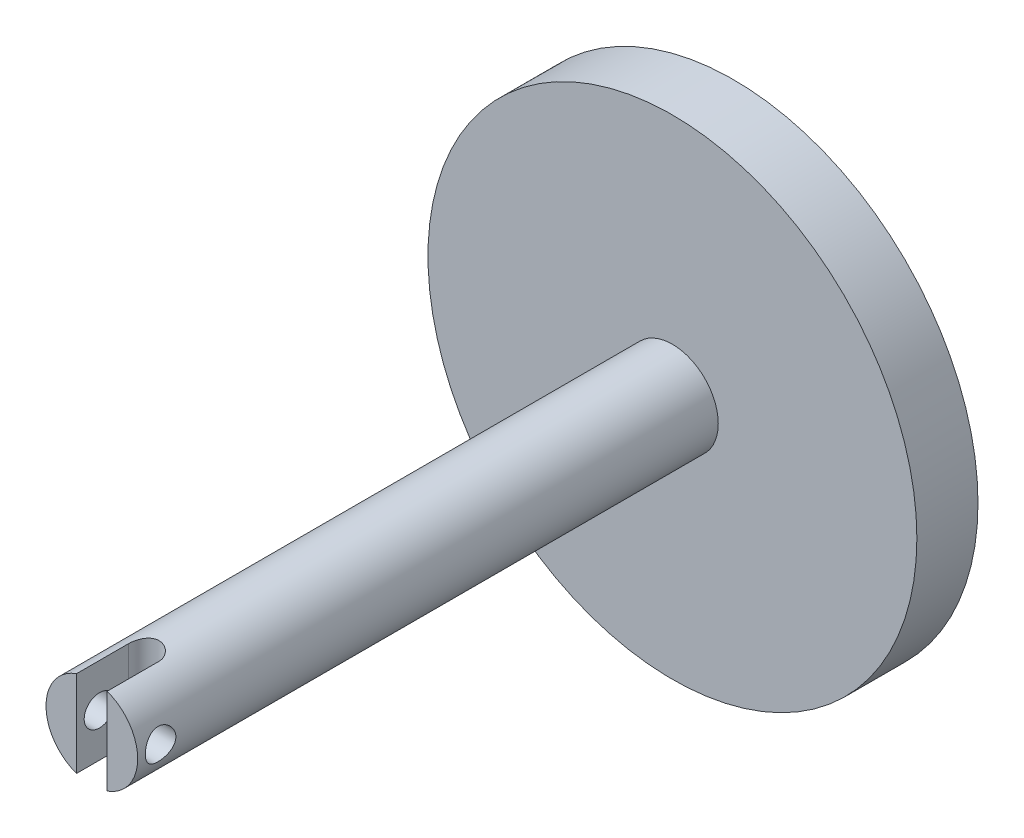
SolidWorks part; units mm, degrees
ref_plane "Front Plane" through (0, 0, 0) normal (0, 0, 1) x (1, 0, 0)
ref_plane "Top Plane" through (0, 0, 0) normal (0, 1, 0) x (1, 0, 0)
ref_plane "Right Plane" through (0, 0, 0) normal (1, 0, 0) x (0, 0, -1)
sketch "Sketch1" plane through (0, 0, 0) normal (0, 0, 1) x (1, 0, 0)
  circle A0 centre (0, 0) radius 40
  dimension "D1" = 80
extrude "Boss-Extrude1" add sketch "Sketch1" along normal blind 10
sketch "Sketch2" plane through (0, 0, 10) normal (0, 0, 1) x (1, 0, 0)
  line L0 (0, 0) -> (0, 40) construction
  line L1 (0, 40) -> (0, -40) construction
  line L2 (0, 0) -> (-40, 0) construction
  line L3 (-40, 0) -> (40, 0) construction
  line L4 (0, 0) -> (-28.2843, 28.2843) construction
  line L5 (-28.2843, 28.2843) -> (28.2843, -28.2843) construction
  line L6 (28.2843, -28.2843) -> (-28.2843, -28.2843) construction
  line L7 (-28.2843, -28.2843) -> (28.2843, 28.2843) construction
  line L8 (28.2843, 28.2843) -> (28.2843, -28.2843) construction
  line L9 (-28.2843, 28.2843) -> (-28.2843, -28.2843) construction
  line L10 (-28.2843, 28.2843) -> (28.2843, 28.2843) construction
  circle A0 centre (0, 0) radius 40 construction
sketch "Sketch12" plane through (0, 0, 0) normal (0, 0, -1) x (-1, 0, 0)
  circle A0 centre (0, 0) radius 15
  dimension "D1" = 30
extrude "Boss-Extrude3" add sketch "Sketch12" along normal blind 10
sketch "Sketch13" plane through (0, 0, 10) normal (0, 0, 1) x (1, 0, 0)
  circle A0 centre (0, 0) radius 7.5
  dimension "D1" = 15
extrude "Boss-Extrude4" add sketch "Sketch13" along normal blind 95
sketch "Sketch14" plane through (0, 0, 0) normal (0, 1, 0) x (1, 0, 0)
  line L1 (0, -105) -> (0, -10) construction
  line L2 (-7.5, -105) -> (7.5, -105) construction
  line L4 (-2.5, -96.5) -> (-2.5, -105) construction
  line L6 (-2.5, -105) -> (2.5, -105)
  line L7 (-2.5, -105) -> (-2.5, -96.5)
  line L9 (2.5, -105) -> (2.5, -96.5)
  arc A0 (2.5, -96.5) -> (-2.5, -96.5) centre (0, -96.5) ccw
  dimension "D1" = 5
  dimension "D2" = 8.5
extrude "Cut-Extrude1" cut sketch "Sketch14" along normal through all
mirror "Mirror4" about plane through (0, 0, 0) normal (0, 1, 0) of "Cut-Extrude1"
sketch "Sketch17" plane through (0, 0, 0) normal (1, 0, 0) x (0, 0, -1)
  line L0 (-105, 0) -> (-10, 0) construction
  line L1 (-105, 7.0711) -> (-105, -7.0711) construction
  circle A0 centre (-101.25, 0) radius 2.5
  dimension "D1" = 5
  dimension "D2" = 3.75
extrude "Cut-Extrude3" cut sketch "Sketch17" against normal through all
mirror "Mirror6" about plane through (0, 0, 0) normal (1, 0, 0) of "Cut-Extrude3"
sketch "Sketch18" plane through (0, 0, 0) normal (1, 0, 0) x (0, 0, -1)
  line L0 (-10, 0) -> (0, 0) construction
  circle A0 centre (-5, 0) radius 1.5
  dimension "D1" = 3
  dimension "D2" = 5
extrude "Cut-Extrude4" cut sketch "Sketch18" against normal through all
